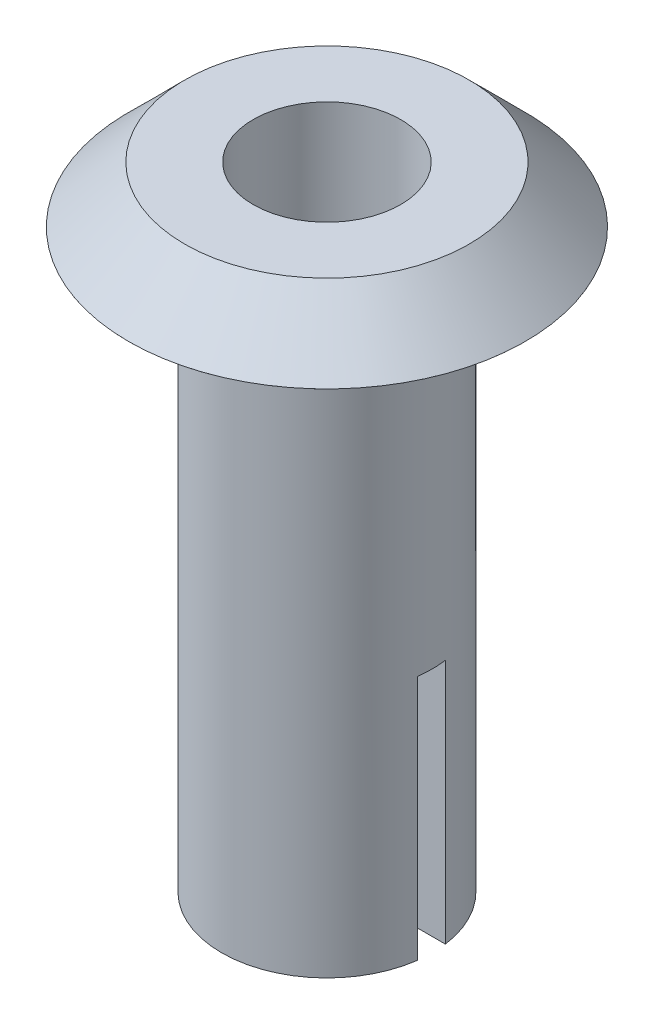
SolidWorks part; units mm, degrees
ref_plane "Alzado" through (0, 0, 0) normal (0, 0, 1) x (1, 0, 0)
ref_plane "Planta" through (0, 0, 0) normal (0, 1, 0) x (1, 0, 0)
ref_plane "Vista lateral" through (0, 0, 0) normal (1, 0, 0) x (0, 0, -1)
sketch "Croquis1" plane through (0, 0, 0) normal (0, 1, 0) x (1, 0, 0)
  circle A0 centre (0, 0) radius 1.5
extrude "Saliente-Extruir1" add sketch "Croquis1" along normal blind 9
sketch "Croquis2" plane through (0, 9, 0) normal (0, 1, 0) x (1, 0, 0)
  circle A0 centre (0, 0) radius 2.825
extrude "Saliente-Extruir2" add sketch "Croquis2" along normal blind 0.0001 and the other way blind 0.8
chamfer "Chaflán1" distance 0.8 angle 45 1 edges at (0, 9.0001, 2.825)
sketch "Croquis3" plane through (0, 9.0001, 0) normal (0, 1, 0) x (1, 0, 0)
  circle A0 centre (0, 0) radius 1.05
extrude "Cortar-Extruir1" cut sketch "Croquis3" against normal blind 7.5
fillet "Redondeo2" radius 0.8 1 edges at (0, 1.5001, 1.05)
sketch "Croquis6" plane through (0, 0, 0) normal (0, -1, 0) x (-1, 0, 0)
  line L1 (1.5, -0.2) -> (-1.5, -0.2)
  line L2 (1.5, -0.2) -> (1.5, 0.2)
  line L3 (1.5, 0.2) -> (-1.5, 0.2)
  line L4 (-1.5, -0.2) -> (-1.5, 0.2)
  line L5 (1.5, -0.2) -> (-1.5, 0.2) construction
  line L6 (1.5, 0.2) -> (-1.5, -0.2) construction
  point P0 (0, 0)
extrude "Cortar-Extruir4" cut sketch "Croquis6" against normal blind 3.5
